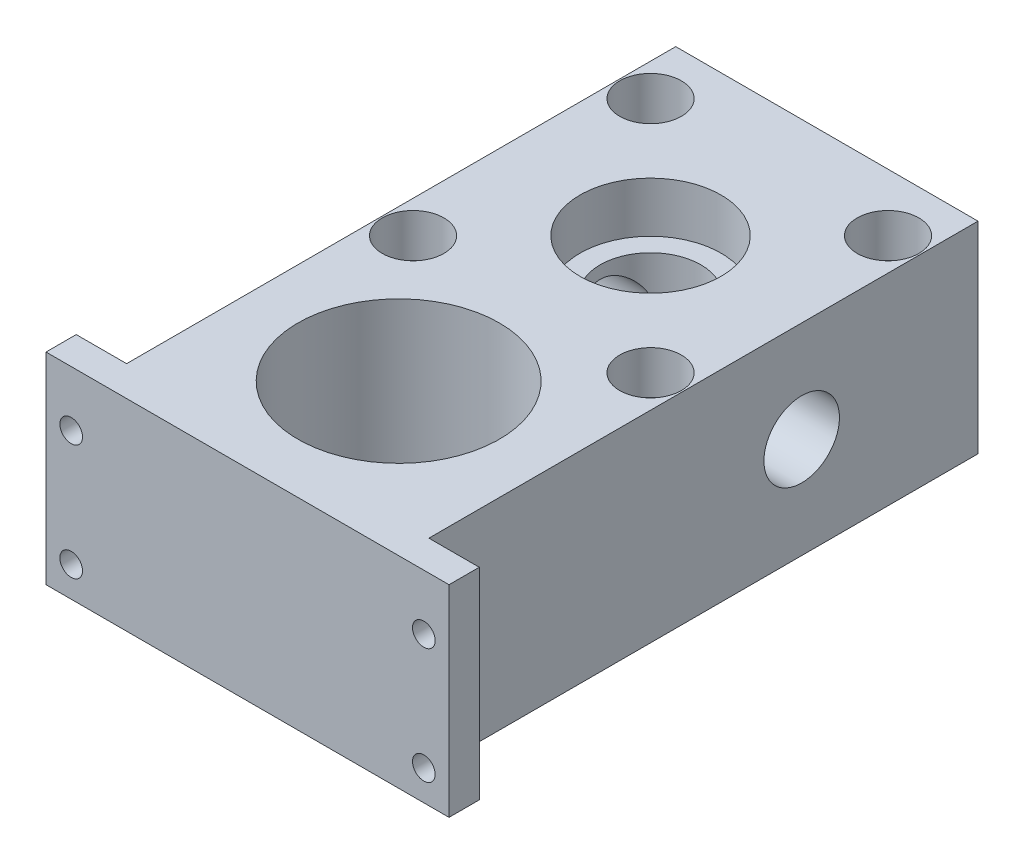
SolidWorks part; units mm, degrees
ref_plane "Front" through (0, 0, 0) normal (0, 0, 1) x (1, 0, 0)
ref_plane "Top" through (0, 0, 0) normal (0, 1, 0) x (1, 0, 0)
ref_plane "Right" through (0, 0, 0) normal (1, 0, 0) x (0, 0, -1)
sketch "Sketch1" plane through (0, 0, 0) normal (0, 1, 0) x (1, 0, 0)
  line L0 (0, 0) -> (-10, 0)
  line L1 (-10, 0) -> (-10, -6)
  line L2 (0, 0) -> (0, 109)
  line L3 (0, 109) -> (60, 109)
  line L4 (60, 0) -> (60, 109)
  line L5 (-10, -6) -> (70, -6)
  line L6 (70, -6) -> (70, 0)
  line L7 (60, 0) -> (70, 0)
  line L8 (30, 109) -> (30, 74) construction
  circle A0 centre (30, 74) radius 10
  dimension "D5" = 20
  dimension "D6" = 80
  dimension "D1" = 60
  dimension "D2" = 109
  dimension "D3" = 6
  dimension "D4" = 80
extrude "Boss-Extrude1" add sketch "Sketch1" along normal blind 40
sketch "Sketch2" plane through (0, 0, 0) normal (0, -1, 0) x (1, 0, 0)
  circle A0 centre (30, -74) radius 14
  dimension "D1" = 28
extrude "Cut-Extrude1" cut sketch "Sketch2" against normal blind 12
sketch "Sketch3" plane through (0, 40, 0) normal (0, 1, 0) x (1, 0, 0)
  circle A0 centre (30, 74) radius 14
  circle A1 centre (30, 74) radius 14 construction
extrude "Cut-Extrude2" cut sketch "Sketch3" against normal blind 10
sketch "Sketch5" plane through (0, 0, 0) normal (0, -1, 0) x (1, 0, 0)
  circle A0 centre (30, -74) radius 19.05
  dimension "D1" = 38.1
extrude "Cut-Extrude3" cut sketch "Sketch5" against normal blind 2
hole_wizard "CBORE for M5 Hex Head Bolt1" positions "Sketch8" profile "Sketch7" counterbore size "M5" standard "Ansi Metric" end condition through all
sketch "Sketch8" plane through (0, 40, 0) normal (0, 1, 0) x (-1, 0, 0)
  line L0 (-6.43, -50.43) -> (-6.43, -97.57) construction
  line L1 (-6.43, -97.57) -> (-53.57, -97.57) construction
  line L2 (-53.57, -97.57) -> (-53.57, -50.43) construction
  line L3 (-53.57, -50.43) -> (-6.43, -50.43) construction
  line L4 (-60, -109) -> (0, -109) construction
  line L6 (-6.43, -50.43) -> (-53.57, -97.57) construction
  line L7 (-30, -97.57) -> (-30, -74) construction
  circle A0 centre (-30, -74) radius 14 construction
  point P0 (-6.43, -97.57)
  point P1 (-6.43, -50.43)
  point P3 (-53.57, -50.43)
  point P5 (-53.57, -97.57)
  dimension "D2" = 23.57
  dimension "D1" = 47.14
sketch "Sketch7" plane through (6.43, 40, -97.57) normal (1, 0, 0) x (0, 0, 1)
  line L0 (0, 0) -> (0, 40)
  line L1 (0, 40) -> (2.75, 40)
  line L3 (2.75, 40) -> (2.75, 8.58)
  line L4 (2.75, 8.58) -> (6.12, 8.58)
  line L5 (6.12, 8.58) -> (6.12, 0)
  line L7 (6.12, 0) -> (0, 0)
  line L11 (0, -6.35) -> (0, 107.95) construction
  dimension "Thru Hole Dia." = 5.5
  dimension "Thru Hole Depth" = 40
  dimension "C'Bore Dia." = 12.24
  dimension "C'Bore Depth" = 8.58
hole_wizard "CSK for M4 Flat Head Machine Screw1" positions "Sketch11" profile "Sketch10" countersink size "M4" standard "Ansi Metric" end condition through all
sketch "Sketch11" plane through (0, 0, 0) normal (0, 0, -1) x (-1, 0, 0)
  line L0 (-70, 0) -> (-60, 0) construction
  line L1 (-70, 40) -> (-70, 0) construction
  point P0 (-65, 6)
  dimension "D1" = 6
  dimension "D2" = 5
sketch "Sketch10" plane through (65, 6, 0) normal (1, 0, 0) x (0, 1, 0)
  line L0 (0, 0) -> (0, 6)
  line L1 (0, 6) -> (2.25, 6)
  line L2 (2.25, 6) -> (2.25, 2.45)
  line L3 (2.25, 2.45) -> (4.7, 0)
  line L5 (4.7, 0) -> (0, 0)
  line L6 (-2.25, 2.45) -> (-4.7, 0) construction
  line L11 (0, -6.35) -> (0, 107.95) construction
  dimension "Thru Hole Dia." = 4.5
  dimension "Thru Hole Depth" = 6
  dimension "Near C'Sink Dia." = 9.4
  dimension "Near C'Sink Angle" = 90
pattern_linear "LPattern1" count 2 spacing 23 along (0, 1, 0) count 2 spacing 70 along (-1, 0, 0) of "CSK for M4 Flat Head Machine Screw1"
ref_plane "Plane1" through (30, 12, -74) normal (-1, 0, 0) x (0, 0, -1)
sketch "Sketch13" plane through (60, 0, 0) normal (1, 0, 0) x (0, 0, -1)
  line L0 (109, 20) -> (74, 20) construction
  line L1 (109, 40) -> (109, 0) construction
  circle A0 centre (74, 20) radius 7.5
  dimension "D2" = 15
  dimension "D1" = 35
extrude "Cut-Extrude4" cut sketch "Sketch13" against normal through all
sketch "Sketch14" plane through (0, 0, 0) normal (0, -1, 0) x (1, 0, 0)
  line L0 (30, 6) -> (30, -24) construction
  line L1 (-10, 6) -> (70, 6) construction
  circle A0 centre (30, -24) radius 20.0007
  dimension "D1" = 40.0013
  dimension "D2" = 30
extrude "Cut-Extrude5" cut sketch "Sketch14" against normal through all
